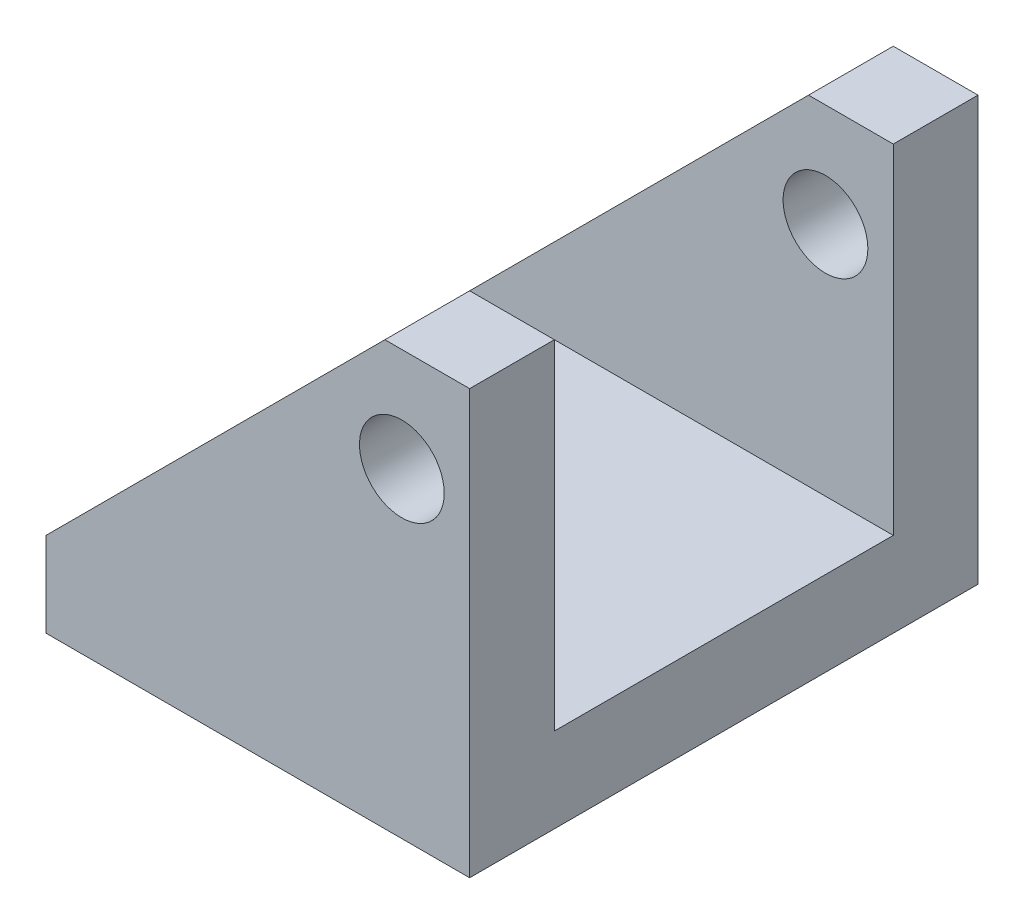
SolidWorks part; units mm, degrees
ref_plane "Front Plane" through (0, 0, 0) normal (0, 0, 1) x (1, 0, 0)
ref_plane "Top Plane" through (0, 0, 0) normal (0, 1, 0) x (1, 0, 0)
ref_plane "Right Plane" through (0, 0, 0) normal (1, 0, 0) x (0, 0, -1)
sketch "Sketch1" plane through (0, 0, 0) normal (0, 0, 1) x (1, 0, 0)
  line L0 (-31.75, 0) -> (0, 0)
  line L1 (0, 0) -> (0, 31.75)
  line L2 (-31.75, 0) -> (-31.75, 6.35)
  line L3 (-31.75, 6.35) -> (-6.35, 31.75)
  line L4 (-6.35, 31.75) -> (0, 31.75)
  dimension "D1" = 31.75
  dimension "D2" = 31.75
  dimension "D3" = 6.35
  dimension "D4" = 6.35
extrude "Boss-Extrude1" add sketch "Sketch1" along normal blind 38.1
sketch "Sketch2" plane through (0, 0, 0) normal (1, 0, 0) x (0, 0, -1)
  line L0 (-38.1, 31.75) -> (0, 31.75) construction
  line L1 (-31.75, 31.75) -> (-6.35, 31.75)
  line L2 (-31.75, 31.75) -> (-31.75, 6.35)
  line L3 (-31.75, 6.35) -> (-6.35, 6.35)
  line L4 (-6.35, 31.75) -> (-6.35, 6.35)
  line L5 (-38.1, 0) -> (-38.1, 31.75) construction
  line L6 (0, 0) -> (0, 31.75) construction
  line L7 (-38.1, 0) -> (0, 0) construction
  dimension "D1" = 6.35
  dimension "D2" = 6.35
  dimension "D3" = 6.35
extrude "Cut-Extrude1" cut sketch "Sketch2" against normal blind 38.1
sketch "Sketch3" plane through (0, 0, 38.1) normal (0, 0, 1) x (1, 0, 0)
  line L0 (-31.75, 0) -> (0, 0) construction
  line L1 (0, 0) -> (0, 31.75) construction
  circle A0 centre (-5.08, 24) radius 3.175
  dimension "D1" = 6.35
  dimension "D2" = 24
  dimension "D3" = 5.08
extrude "Cut-Extrude2" cut sketch "Sketch3" against normal blind 38.1
